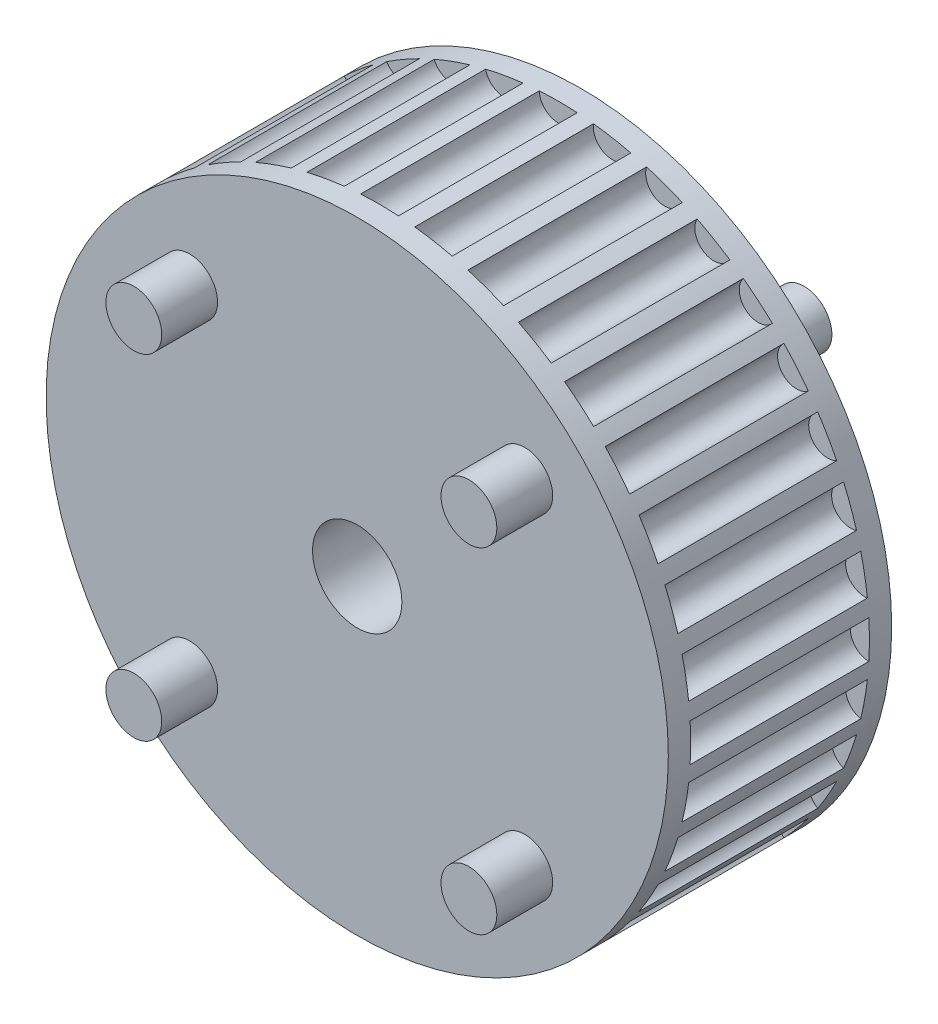
SolidWorks part; units mm, degrees
material "Custom Plastic"
ref_plane "Front Plane" through (0, 0, 0) normal (0, 0, 1) x (1, 0, 0)
ref_plane "Top Plane" through (0, 0, 0) normal (0, 1, 0) x (1, 0, 0)
ref_plane "Right Plane" through (0, 0, 0) normal (1, 0, 0) x (0, 0, -1)
sketch "Sketch1" plane through (0, 0, 0) normal (0, 0, 1) x (1, 0, 0)
  circle A0 centre (0, 0) radius 4
  circle A1 centre (0, 0) radius 27.8521
  dimension "D1" = 8
  dimension "D2" = 55.7042
extrude "Boss-Extrude1" add sketch "Sketch1" along normal blind 20
ref_plane "Plane1" through (0, 0, 10) normal (0, 0, 1) x (1, 0, 0)
sketch "Sketch2" plane through (0, 0, 10) normal (0, 0, 1) x (1, 0, 0)
  line L0 (15, 15) -> (-15, -15) construction
  line L1 (-15, -15) -> (15, -15) construction
  line L2 (-15, -15) -> (-15, 15) construction
  line L3 (-15, 15) -> (15, 15) construction
  line L4 (15, -15) -> (15, 15) construction
  circle A0 centre (-15, 15) radius 2.5
  circle A1 centre (15, 15) radius 2.5
  circle A2 centre (15, -15) radius 2.5
  circle A3 centre (-15, -15) radius 2.5
  point P4 (0, 0)
  dimension "D1" = 5
  dimension "D2" = 30
extrude "Boss-Extrude2" add sketch "Sketch2" along normal blind 15 and the other way blind 15
sketch "Sketch4" plane through (0, 0, 10) normal (0, 0, 1) x (1, 0, 0)
  circle A32 centre (0, 0) radius 27.8521 construction
  circle A33 centre (27.8521, 0) radius 1.7
  circle A34 centre (27.429, -4.8365) radius 1.7
  circle A35 centre (26.1724, -9.526) radius 1.7
  circle A36 centre (24.1206, -13.9261) radius 1.7
  circle A37 centre (21.336, -17.903) radius 1.7
  circle A38 centre (17.903, -21.336) radius 1.7
  circle A39 centre (13.9261, -24.1206) radius 1.7
  circle A40 centre (9.526, -26.1724) radius 1.7
  circle A41 centre (4.8365, -27.429) radius 1.7
  circle A42 centre (0, -27.8521) radius 1.7
  circle A43 centre (-4.8365, -27.429) radius 1.7
  circle A44 centre (-9.526, -26.1724) radius 1.7
  circle A45 centre (-13.9261, -24.1206) radius 1.7
  circle A46 centre (-17.903, -21.336) radius 1.7
  circle A47 centre (-21.336, -17.903) radius 1.7
  circle A48 centre (-24.1206, -13.9261) radius 1.7
  circle A49 centre (-26.1724, -9.526) radius 1.7
  circle A50 centre (-27.429, -4.8365) radius 1.7
  circle A51 centre (-27.8521, 0) radius 1.7
  circle A52 centre (-27.429, 4.8365) radius 1.7
  circle A53 centre (-26.1724, 9.526) radius 1.7
  circle A54 centre (-24.1206, 13.9261) radius 1.7
  circle A55 centre (-21.336, 17.903) radius 1.7
  circle A56 centre (-17.903, 21.336) radius 1.7
  circle A57 centre (-13.9261, 24.1206) radius 1.7
  circle A58 centre (-9.526, 26.1724) radius 1.7
  circle A59 centre (-4.8365, 27.429) radius 1.7
  circle A60 centre (0, 27.8521) radius 1.7
  circle A61 centre (4.8365, 27.429) radius 1.7
  circle A62 centre (9.526, 26.1724) radius 1.7
  circle A63 centre (13.9261, 24.1206) radius 1.7
  circle A64 centre (17.903, 21.336) radius 1.7
  circle A65 centre (21.336, 17.903) radius 1.7
  circle A66 centre (24.1206, 13.9261) radius 1.7
  circle A67 centre (26.1724, 9.526) radius 1.7
  circle A68 centre (27.429, 4.8365) radius 1.7
  point P6 (0, 0)
  point P7 (24.1206, -13.9261)
  point P77 (0, 0)
  dimension "D1" = 55.7042
  dimension "D2" = 3.4
extrude "Cut-Extrude1" cut sketch "Sketch4" against normal mid plane 16
